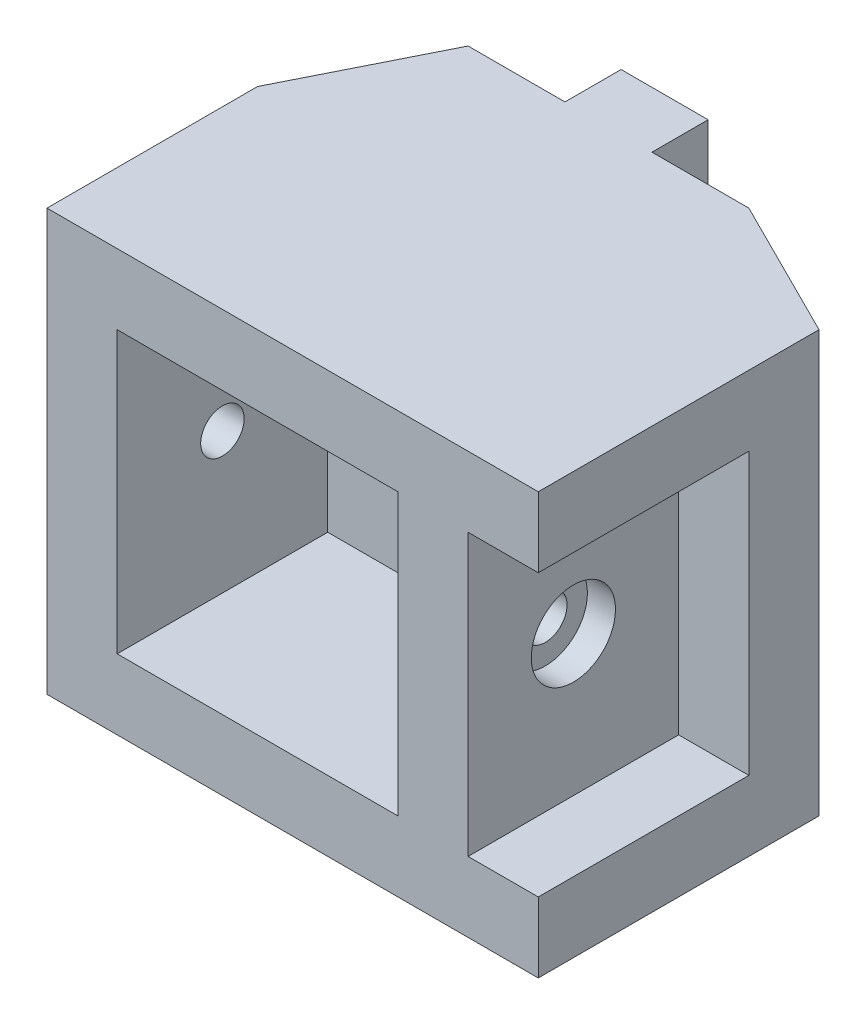
SolidWorks part; units mm, degrees
ref_plane "Front Plane" through (0, 0, 0) normal (0, 0, 1) x (1, 0, 0)
ref_plane "Top Plane" through (0, 0, 0) normal (0, 1, 0) x (1, 0, 0)
ref_plane "Right Plane" through (0, 0, 0) normal (1, 0, 0) x (0, 0, -1)
other "Configuration Table"
sketch "草图1" plane through (0, 0, 0) normal (0, 0, 1) x (1, 0, 0)
  line L0 (-15, 22) -> (-15, -22)
  line L1 (0, 22) -> (15, 22)
  line L2 (0, 22) -> (-15, 22)
  line L3 (15, 22) -> (15, -22)
  line L4 (15, -22) -> (-15, -22)
extrude "凸台-拉伸1" add sketch "草图1" along normal blind 14 contours L0 L4 L3 L1 L2
sketch "草图2" plane through (0, 22, 0) normal (0, 1, 0) x (1, 0, 0)
  line L3 (10, -4) -> (15, -14)
  line L4 (15, -14) -> (-15, -14)
  line L6 (-15, -14) -> (-10, -4)
  line L8 (3.1, -4) -> (3.1, 0)
  line L9 (-15, 0) -> (15, 0) construction
  line L10 (3.1, 0) -> (15, 0)
  line L11 (15, 0) -> (15, -14)
  line L12 (10, -4) -> (3.1, -4)
  line L13 (-3.1, -4) -> (-10, -4)
  line L14 (-15, -14) -> (-15, 0)
  line L15 (-15, 0) -> (-3.1, 0)
  line L16 (-3.1, 0) -> (-3.1, -4)
  line M14 (15, 0) -> (-15, 0)
  line M15 (-15, 0) -> (-15, -14)
  line M17 (15, -14) -> (15, 0)
extrude "切除-拉伸1" cut sketch "草图2" against normal blind 44 contours L16 L6 L13 M14 M15 | L12 L3 L8 M17 M14
sketch "草图3" plane through (0, 0, 0) normal (0, 0, -1) x (-1, 0, 0)
  line L2 (-3.1, 3.1) -> (-3.1, -3.1)
  line L4 (3.1, -22) -> (3.1, 22) construction
  line L5 (3.1, 3.1) -> (-3.1, 3.1)
  line L6 (-3.1, -22) -> (-3.1, 22) construction
  line L9 (-3.1, -3.1) -> (3.1, -3.1)
  line L10 (3.1, -22) -> (3.1, 22) construction
  line L11 (3.1, -3.1) -> (3.1, 3.1)
extrude "切除-拉伸2" cut sketch "草图3" against normal blind 4 contours L2 L9 L11 L5
sketch "草图4" plane through (0, 0, 14) normal (0, 0, 1) x (1, 0, 0)
  circle A0 centre (0, 0) radius 4
extrude "切除-拉伸3" cut sketch "草图4" against normal blind 5
sketch "草图5" plane through (0, 0, 9) normal (0, 0, 1) x (1, 0, 0)
  circle A0 centre (0, 0) radius 2.6
extrude "切除-拉伸4" cut sketch "草图5" against normal blind 5 contours A0
sketch "草图7" plane through (0, -22, 0) normal (0, -1, 0) x (1, 0, 0)
  line L3 (10, 4) -> (3.1, 4) construction
  line L5 (15, 14) -> (20, 14)
  line L8 (10, 4) -> (20, 9)
  line L9 (20, 9) -> (20, 14)
  line L10 (10, 4) -> (10, 14)
  line L11 (15, 14) -> (-15, 14) construction
  line L12 (10, 14) -> (15, 14)
extrude "凸台-拉伸2" add sketch "草图7" against normal blind 44 contours L12 L5 L9 L8 L10
sketch "草图8" plane through (0, 0, 14) normal (0, 0, 1) x (1, 0, 0)
  line L2 (-10, 10) -> (-10, 15)
  line L3 (-10, 10) -> (-15, 10)
  line L4 (0, 10) -> (10, 10)
  line L5 (10, 10) -> (10, 0)
  line L6 (0, -10) -> (10, -10)
  line L7 (10, -10) -> (10, 0)
  line L8 (0, -10) -> (-10, -10)
  line L9 (-10, -10) -> (-10, 0)
  line L10 (0, 10) -> (-10, 10)
  line L11 (-10, 10) -> (-10, 0)
  line L12 (-10, -10) -> (-10, -15)
  line L13 (-10, -10) -> (-15, -10)
  line L14 (10, -10) -> (15, -10)
  line L15 (10, -10) -> (10, -15)
  line L16 (10, 10) -> (10, 15)
  line L17 (10, 10) -> (15, 10)
  line L18 (-10, -15) -> (10, -15)
  line L19 (10, -15) -> (15, -15)
  line L20 (15, -15) -> (15, -10)
  line L21 (-15, -10) -> (-15, 10)
  line L22 (-10, 15) -> (10, 15)
  line L23 (15, 10) -> (15, 15)
  line L24 (15, 15) -> (10, 15)
  line L25 (15, 10) -> (15, -10)
  line L26 (-10, -15) -> (-15, -15)
  line L27 (-15, 22) -> (-15, -22) construction
  line L28 (-15, -15) -> (-15, -10)
  line L29 (-15, 10) -> (-15, 15)
  line L30 (-15, 15) -> (-10, 15)
  line L31 (15, -15) -> (20, -15)
  line L32 (20, 22) -> (20, -22) construction
  line L33 (20, -15) -> (20, -10)
  line L34 (20, -10) -> (15, -10)
  line L35 (15, 10) -> (20, 10)
  line L36 (20, 10) -> (20, 15)
  line L37 (20, 15) -> (15, 15)
  line M22 (-15, 22) -> (-15, -22)
  line M24 (20, -22) -> (20, 22)
extrude "凸台-拉伸4" add sketch "草图8" along normal blind 15 contours L26 L12 L13 M22 | L12 L18 L15 L6 L8 | L13 L9 L11 L3 M22 | L30 L3 L2 M22 | L22 L2 L10 L4 L16 | L23 L24 L16 L17 | L25 L17 L5 L7 L14 | L19 L20 L14 L15 | L34 L20 L31 M24 | L37 L23 L35 M24
sketch "草图9" plane through (0, 15, 0) normal (0, 1, 0) x (1, 0, 0)
  line L0 (20, -29) -> (20, -14) construction
  line L1 (-15, -29) -> (20, -29)
  line L2 (-15, -29) -> (-15, -24)
  line L3 (-15, -24) -> (20, -24)
  line L4 (20, -29) -> (20, -24)
extrude "凸台-拉伸5" add sketch "草图9" along normal blind 7 contours L2 L1 L4 L3
sketch "草图13" plane through (-10, 0, 0) normal (1, 0, 0) x (0, 0, -1)
  line L0 (-29, 10) -> (-14, -10)
  circle A0 centre (-21.5, 0) radius 1.55
extrude "切除-拉伸6" cut sketch "草图13" against normal blind 10 contours L0 A0 | L0 A0
sketch "草图14" plane through (-15, 0, 0) normal (-1, 0, 0) x (0, 0, 1)
  circle A0 centre (21.5, 0) radius 1.55
extrude "切除-拉伸7" cut sketch "草图14" against normal blind 30 contours A0
sketch "草图15" plane through (15, 0, 0) normal (1, 0, 0) x (0, 0, -1)
  circle A0 centre (-21.5, 0) radius 3
extrude "切除-拉伸8" cut sketch "草图15" against normal blind 2
sketch "草图16" plane through (-15, 0, 0) normal (-1, 0, 0) x (0, 0, 1)
  circle A0 centre (21.5, 0) radius 3
extrude "切除-拉伸9" cut sketch "草图16" against normal blind 2
sketch "草图17" plane through (0, 0, 29) normal (0, 0, 1) x (1, 0, 0)
  line L0 (20, 10) -> (20, 22) construction
  line L1 (-15, 22) -> (20, 22)
  line L2 (-15, 22) -> (-15, 15)
  line L3 (-15, 15) -> (20, 15)
  line L4 (20, 22) -> (20, 15)
extrude "切除-拉伸10" cut sketch "草图17" against normal blind 10
sketch "草图18" plane through (0, 0, 14) normal (0, 0, 1) x (1, 0, 0)
  line L1 (-15, 22) -> (20, 22)
  line L2 (-15, 22) -> (-15, 15)
  line L3 (-15, 15) -> (20, 15)
  line L4 (20, 22) -> (20, 15)
  line L5 (-15, -22) -> (20, -22)
  line L6 (-15, -22) -> (-15, -15)
  line L7 (-15, -15) -> (20, -15)
  line L8 (20, -22) -> (20, -15)
extrude "切除-拉伸11" cut sketch "草图18" against normal blind 20 contours L2 L1 L4 L3 | L6 L5 L8 L7
